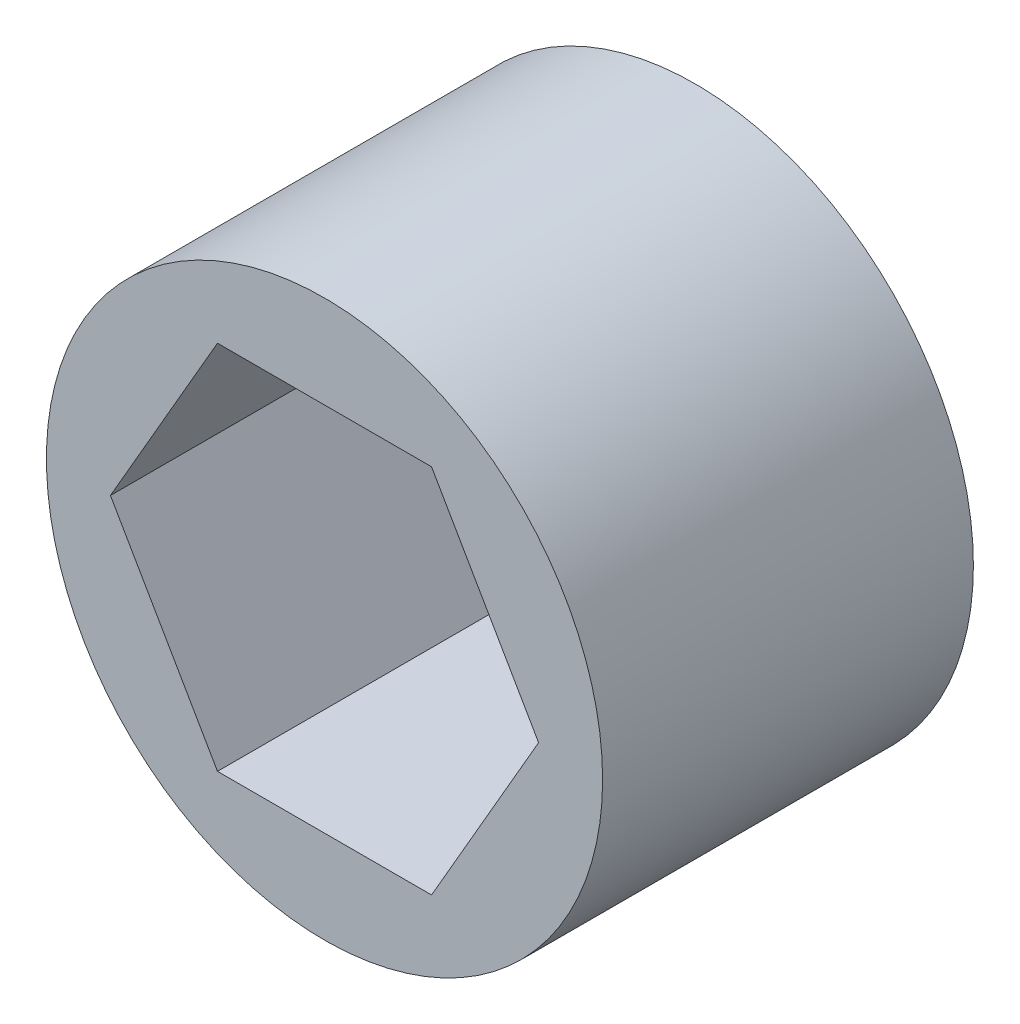
SolidWorks part; units mm, degrees
material "PET"
ref_plane "Front Plane" through (0, 0, 0) normal (0, 0, 1) x (1, 0, 0)
ref_plane "Top Plane" through (0, 0, 0) normal (0, 1, 0) x (1, 0, 0)
ref_plane "Right Plane" through (0, 0, 0) normal (1, 0, 0) x (0, 0, -1)
sketch "Sketch1" plane through (0, 0, 0) normal (0, 0, 1) x (1, 0, 0)
  line L1 (7.3323, 0) -> (3.6662, 6.35)
  line L2 (3.6662, 6.35) -> (-3.6662, 6.35)
  line L3 (-3.6662, 6.35) -> (-7.3323, 0)
  line L4 (-7.3323, 0) -> (-3.6662, -6.35)
  line L5 (-3.6662, -6.35) -> (3.6662, -6.35)
  line L6 (3.6662, -6.35) -> (7.3323, 0)
  circle A0 centre (0, 0) radius 9.525
  circle A1 centre (0, 0) radius 6.35 construction
  point P3 (0, 0)
  dimension "D1" = 12.7
  dimension "D2" = 19.05
extrude "Boss-Extrude1" add sketch "Sketch1" along normal blind 12.7
